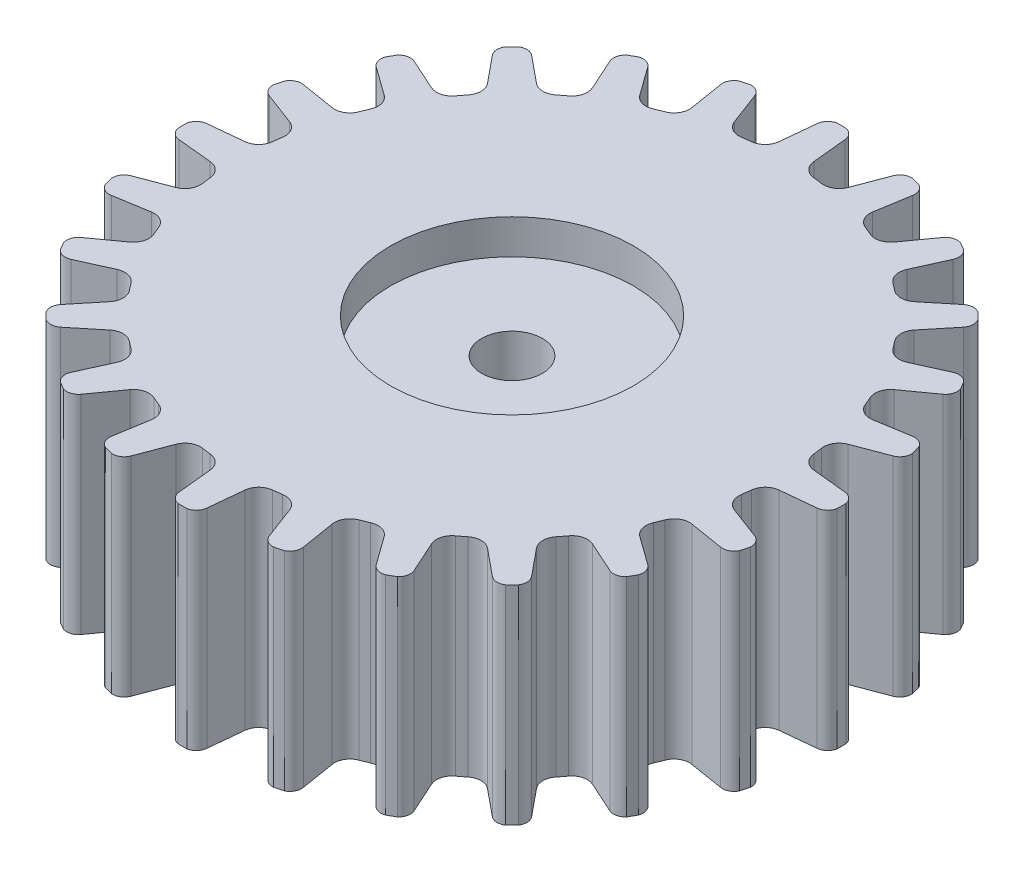
SolidWorks part; units mm, degrees
ref_plane "Front Plane" through (0, 0, 0) normal (0, 0, 1) x (1, 0, 0)
ref_plane "Top Plane" through (0, 0, 0) normal (0, 1, 0) x (1, 0, 0)
ref_plane "Right Plane" through (0, 0, 0) normal (1, 0, 0) x (0, 0, -1)
sketch "Sketch1" plane through (0, 0, 0) normal (0, 1, 0) x (1, 0, 0)
  circle A0 centre (0, 0) radius 2.45
  circle A1 centre (0, 0) radius 9.5
  dimension "D1" = 4.9
  dimension "D2" = 19
extrude "Boss-Extrude1" add sketch "Sketch1" along normal blind 6
sketch "Sketch2" plane through (0, 6, 0) normal (0, 1, 0) x (1, 0, 0)
  line L0 (0, 0) -> (0, 10.7871) construction
  line L1 (0.5, 8.2) -> (0.4, 9.2)
  line L2 (-0.5, 8.2) -> (-0.4, 9.2)
  line L3 (2.6053, 7.7912) -> (2.7675, 8.783)
  line L4 (1.6394, 8.05) -> (1.9948, 8.99)
  line L5 (4.533, 6.8514) -> (4.9464, 7.7674)
  line L6 (3.667, 7.3514) -> (4.2536, 8.1674)
  line L7 (6.1518, 5.4447) -> (6.7882, 6.2225)
  line L8 (5.4447, 6.1518) -> (6.2225, 6.7882)
  line L9 (7.3514, 3.667) -> (8.1674, 4.2536)
  line L10 (6.8514, 4.533) -> (7.7674, 4.9464)
  line L11 (8.05, 1.6394) -> (8.99, 1.9948)
  line L12 (7.7912, 2.6053) -> (8.783, 2.7675)
  line L13 (8.2, -0.5) -> (9.2, -0.4)
  line L14 (8.2, 0.5) -> (9.2, 0.4)
  line L15 (7.7912, -2.6053) -> (8.783, -2.7675)
  line L16 (8.05, -1.6394) -> (8.99, -1.9948)
  line L17 (6.8514, -4.533) -> (7.7674, -4.9464)
  line L18 (7.3514, -3.667) -> (8.1674, -4.2536)
  line L19 (5.4447, -6.1518) -> (6.2225, -6.7882)
  line L20 (6.1518, -5.4447) -> (6.7882, -6.2225)
  line L21 (3.667, -7.3514) -> (4.2536, -8.1674)
  line L22 (4.533, -6.8514) -> (4.9464, -7.7674)
  line L23 (1.6394, -8.05) -> (1.9948, -8.99)
  line L24 (2.6053, -7.7912) -> (2.7675, -8.783)
  line L25 (-0.5, -8.2) -> (-0.4, -9.2)
  line L26 (0.5, -8.2) -> (0.4, -9.2)
  line L27 (-2.6053, -7.7912) -> (-2.7675, -8.783)
  line L28 (-1.6394, -8.05) -> (-1.9948, -8.99)
  line L29 (-4.533, -6.8514) -> (-4.9464, -7.7674)
  line L30 (-3.667, -7.3514) -> (-4.2536, -8.1674)
  line L31 (-6.1518, -5.4447) -> (-6.7882, -6.2225)
  line L32 (-5.4447, -6.1518) -> (-6.2225, -6.7882)
  line L33 (-7.3514, -3.667) -> (-8.1674, -4.2536)
  line L34 (-6.8514, -4.533) -> (-7.7674, -4.9464)
  line L35 (-8.05, -1.6394) -> (-8.99, -1.9948)
  line L36 (-7.7912, -2.6053) -> (-8.783, -2.7675)
  line L37 (-8.2, 0.5) -> (-9.2, 0.4)
  line L38 (-8.2, -0.5) -> (-9.2, -0.4)
  line L39 (-7.7912, 2.6053) -> (-8.783, 2.7675)
  line L40 (-8.05, 1.6394) -> (-8.99, 1.9948)
  line L41 (-6.8514, 4.533) -> (-7.7674, 4.9464)
  line L42 (-7.3514, 3.667) -> (-8.1674, 4.2536)
  line L43 (-5.4447, 6.1518) -> (-6.2225, 6.7882)
  line L44 (-6.1518, 5.4447) -> (-6.7882, 6.2225)
  line L45 (-3.667, 7.3514) -> (-4.2536, 8.1674)
  line L46 (-4.533, 6.8514) -> (-4.9464, 7.7674)
  line L47 (-1.6394, 8.05) -> (-1.9948, 8.99)
  line L48 (-2.6053, 7.7912) -> (-2.7675, 8.783)
  arc A0 (2.8881, 7.3013) -> (3.1206, 7.205) centre (0, 0) cw
  arc A2 (0.9, 7.8) -> (1.1495, 7.7672) centre (0, 0) cw
  arc A3 (0.5, 8.2) -> (0.9, 7.8) centre (0.9444, 8.2444) ccw
  arc A4 (0, 9.5) -> (0.4, 9.2) centre (0.0622, 9.1662) cw
  arc A5 (-0.5, 8.2) -> (-0.9, 7.8) centre (-0.9444, 8.2444) cw
  arc A6 (0, 9.5) -> (-0.4, 9.2) centre (-0.0622, 9.1662) ccw
  arc A7 (2.6053, 7.7912) -> (2.8881, 7.3013) centre (3.0461, 7.7191) ccw
  arc A8 (2.4588, 9.1763) -> (2.7675, 8.783) centre (2.4324, 8.8378) cw
  arc A9 (1.6394, 8.05) -> (1.1495, 7.7672) centre (1.2216, 8.208) cw
  arc A10 (2.4588, 9.1763) -> (1.9948, 8.99) centre (2.3123, 8.87) ccw
  arc A11 (4.6794, 6.305) -> (4.879, 6.1518) centre (0, 0) cw
  arc A12 (4.533, 6.8514) -> (4.6794, 6.305) centre (4.9401, 6.6677) ccw
  arc A13 (4.75, 8.2272) -> (4.9464, 7.7674) centre (4.6369, 7.9071) cw
  arc A14 (3.667, 7.3514) -> (3.1206, 7.205) centre (3.3043, 7.6121) cw
  arc A15 (4.75, 8.2272) -> (4.2536, 8.1674) centre (4.5293, 7.9693) ccw
  arc A16 (6.1518, 4.879) -> (6.305, 4.6794) centre (0, 0) cw
  arc A17 (6.1518, 5.4447) -> (6.1518, 4.879) centre (6.4975, 5.1619) ccw
  arc A18 (6.7175, 6.7175) -> (6.7882, 6.2225) centre (6.5254, 6.4375) cw
  arc A19 (5.4447, 6.1518) -> (4.879, 6.1518) centre (5.1619, 6.4975) cw
  arc A20 (6.7175, 6.7175) -> (6.2225, 6.7882) centre (6.4375, 6.5254) ccw
  arc A21 (7.205, 3.1206) -> (7.3013, 2.8881) centre (0, 0) cw
  arc A22 (7.3514, 3.667) -> (7.205, 3.1206) centre (7.6121, 3.3043) ccw
  arc A23 (8.2272, 4.75) -> (8.1674, 4.2536) centre (7.9693, 4.5293) cw
  arc A24 (6.8514, 4.533) -> (6.305, 4.6794) centre (6.6677, 4.9401) cw
  arc A25 (8.2272, 4.75) -> (7.7674, 4.9464) centre (7.9071, 4.6369) ccw
  arc A26 (7.7672, 1.1495) -> (7.8, 0.9) centre (0, 0) cw
  arc A27 (8.05, 1.6394) -> (7.7672, 1.1495) centre (8.208, 1.2216) ccw
  arc A28 (9.1763, 2.4588) -> (8.99, 1.9948) centre (8.87, 2.3123) cw
  arc A29 (7.7912, 2.6053) -> (7.3013, 2.8881) centre (7.7191, 3.0461) cw
  arc A30 (9.1763, 2.4588) -> (8.783, 2.7675) centre (8.8378, 2.4324) ccw
  arc A31 (7.8, -0.9) -> (7.7672, -1.1495) centre (0, 0) cw
  arc A32 (8.2, -0.5) -> (7.8, -0.9) centre (8.2444, -0.9444) ccw
  arc A33 (9.5, 0) -> (9.2, -0.4) centre (9.1662, -0.0622) cw
  arc A34 (8.2, 0.5) -> (7.8, 0.9) centre (8.2444, 0.9444) cw
  arc A35 (9.5, 0) -> (9.2, 0.4) centre (9.1662, 0.0622) ccw
  arc A36 (7.3013, -2.8881) -> (7.205, -3.1206) centre (0, 0) cw
  arc A37 (7.7912, -2.6053) -> (7.3013, -2.8881) centre (7.7191, -3.0461) ccw
  arc A38 (9.1763, -2.4588) -> (8.783, -2.7675) centre (8.8378, -2.4324) cw
  arc A39 (8.05, -1.6394) -> (7.7672, -1.1495) centre (8.208, -1.2216) cw
  arc A40 (9.1763, -2.4588) -> (8.99, -1.9948) centre (8.87, -2.3123) ccw
  arc A41 (6.305, -4.6794) -> (6.1518, -4.879) centre (0, 0) cw
  arc A42 (6.8514, -4.533) -> (6.305, -4.6794) centre (6.6677, -4.9401) ccw
  arc A43 (8.2272, -4.75) -> (7.7674, -4.9464) centre (7.9071, -4.6369) cw
  arc A44 (7.3514, -3.667) -> (7.205, -3.1206) centre (7.6121, -3.3043) cw
  arc A45 (8.2272, -4.75) -> (8.1674, -4.2536) centre (7.9693, -4.5293) ccw
  arc A46 (4.879, -6.1518) -> (4.6794, -6.305) centre (0, 0) cw
  arc A47 (5.4447, -6.1518) -> (4.879, -6.1518) centre (5.1619, -6.4975) ccw
  arc A48 (6.7175, -6.7175) -> (6.2225, -6.7882) centre (6.4375, -6.5254) cw
  arc A49 (6.1518, -5.4447) -> (6.1518, -4.879) centre (6.4975, -5.1619) cw
  arc A50 (6.7175, -6.7175) -> (6.7882, -6.2225) centre (6.5254, -6.4375) ccw
  arc A51 (3.1206, -7.205) -> (2.8881, -7.3013) centre (0, 0) cw
  arc A52 (3.667, -7.3514) -> (3.1206, -7.205) centre (3.3043, -7.6121) ccw
  arc A53 (4.75, -8.2272) -> (4.2536, -8.1674) centre (4.5293, -7.9693) cw
  arc A54 (4.533, -6.8514) -> (4.6794, -6.305) centre (4.9401, -6.6677) cw
  arc A55 (4.75, -8.2272) -> (4.9464, -7.7674) centre (4.6369, -7.9071) ccw
  arc A56 (1.1495, -7.7672) -> (0.9, -7.8) centre (0, 0) cw
  arc A57 (1.6394, -8.05) -> (1.1495, -7.7672) centre (1.2216, -8.208) ccw
  arc A58 (2.4588, -9.1763) -> (1.9948, -8.99) centre (2.3123, -8.87) cw
  arc A59 (2.6053, -7.7912) -> (2.8881, -7.3013) centre (3.0461, -7.7191) cw
  arc A60 (2.4588, -9.1763) -> (2.7675, -8.783) centre (2.4324, -8.8378) ccw
  arc A61 (-0.9, -7.8) -> (-1.1495, -7.7672) centre (0, 0) cw
  arc A62 (-0.5, -8.2) -> (-0.9, -7.8) centre (-0.9444, -8.2444) ccw
  arc A63 (0, -9.5) -> (-0.4, -9.2) centre (-0.0622, -9.1662) cw
  arc A64 (0.5, -8.2) -> (0.9, -7.8) centre (0.9444, -8.2444) cw
  arc A65 (0, -9.5) -> (0.4, -9.2) centre (0.0622, -9.1662) ccw
  arc A66 (-2.8881, -7.3013) -> (-3.1206, -7.205) centre (0, 0) cw
  arc A67 (-2.6053, -7.7912) -> (-2.8881, -7.3013) centre (-3.0461, -7.7191) ccw
  arc A68 (-2.4588, -9.1763) -> (-2.7675, -8.783) centre (-2.4324, -8.8378) cw
  arc A69 (-1.6394, -8.05) -> (-1.1495, -7.7672) centre (-1.2216, -8.208) cw
  arc A70 (-2.4588, -9.1763) -> (-1.9948, -8.99) centre (-2.3123, -8.87) ccw
  arc A71 (-4.6794, -6.305) -> (-4.879, -6.1518) centre (0, 0) cw
  arc A72 (-4.533, -6.8514) -> (-4.6794, -6.305) centre (-4.9401, -6.6677) ccw
  arc A73 (-4.75, -8.2272) -> (-4.9464, -7.7674) centre (-4.6369, -7.9071) cw
  arc A74 (-3.667, -7.3514) -> (-3.1206, -7.205) centre (-3.3043, -7.6121) cw
  arc A75 (-4.75, -8.2272) -> (-4.2536, -8.1674) centre (-4.5293, -7.9693) ccw
  arc A76 (-6.1518, -4.879) -> (-6.305, -4.6794) centre (0, 0) cw
  arc A77 (-6.1518, -5.4447) -> (-6.1518, -4.879) centre (-6.4975, -5.1619) ccw
  arc A78 (-6.7175, -6.7175) -> (-6.7882, -6.2225) centre (-6.5254, -6.4375) cw
  arc A79 (-5.4447, -6.1518) -> (-4.879, -6.1518) centre (-5.1619, -6.4975) cw
  arc A80 (-6.7175, -6.7175) -> (-6.2225, -6.7882) centre (-6.4375, -6.5254) ccw
  arc A81 (-7.205, -3.1206) -> (-7.3013, -2.8881) centre (0, 0) cw
  arc A82 (-7.3514, -3.667) -> (-7.205, -3.1206) centre (-7.6121, -3.3043) ccw
  arc A83 (-8.2272, -4.75) -> (-8.1674, -4.2536) centre (-7.9693, -4.5293) cw
  arc A84 (-6.8514, -4.533) -> (-6.305, -4.6794) centre (-6.6677, -4.9401) cw
  arc A85 (-8.2272, -4.75) -> (-7.7674, -4.9464) centre (-7.9071, -4.6369) ccw
  arc A86 (-7.7672, -1.1495) -> (-7.8, -0.9) centre (0, 0) cw
  arc A87 (-8.05, -1.6394) -> (-7.7672, -1.1495) centre (-8.208, -1.2216) ccw
  arc A88 (-9.1763, -2.4588) -> (-8.99, -1.9948) centre (-8.87, -2.3123) cw
  arc A89 (-7.7912, -2.6053) -> (-7.3013, -2.8881) centre (-7.7191, -3.0461) cw
  arc A90 (-9.1763, -2.4588) -> (-8.783, -2.7675) centre (-8.8378, -2.4324) ccw
  arc A91 (-7.8, 0.9) -> (-7.7672, 1.1495) centre (0, 0) cw
  arc A92 (-8.2, 0.5) -> (-7.8, 0.9) centre (-8.2444, 0.9444) ccw
  arc A93 (-9.5, 0) -> (-9.2, 0.4) centre (-9.1662, 0.0622) cw
  arc A94 (-8.2, -0.5) -> (-7.8, -0.9) centre (-8.2444, -0.9444) cw
  arc A95 (-9.5, 0) -> (-9.2, -0.4) centre (-9.1662, -0.0622) ccw
  arc A96 (-7.3013, 2.8881) -> (-7.205, 3.1206) centre (0, 0) cw
  arc A97 (-7.7912, 2.6053) -> (-7.3013, 2.8881) centre (-7.7191, 3.0461) ccw
  arc A98 (-9.1763, 2.4588) -> (-8.783, 2.7675) centre (-8.8378, 2.4324) cw
  arc A99 (-8.05, 1.6394) -> (-7.7672, 1.1495) centre (-8.208, 1.2216) cw
  arc A100 (-9.1763, 2.4588) -> (-8.99, 1.9948) centre (-8.87, 2.3123) ccw
  arc A101 (-6.305, 4.6794) -> (-6.1518, 4.879) centre (0, 0) cw
  arc A102 (-6.8514, 4.533) -> (-6.305, 4.6794) centre (-6.6677, 4.9401) ccw
  arc A103 (-8.2272, 4.75) -> (-7.7674, 4.9464) centre (-7.9071, 4.6369) cw
  arc A104 (-7.3514, 3.667) -> (-7.205, 3.1206) centre (-7.6121, 3.3043) cw
  arc A105 (-8.2272, 4.75) -> (-8.1674, 4.2536) centre (-7.9693, 4.5293) ccw
  arc A106 (-4.879, 6.1518) -> (-4.6794, 6.305) centre (0, 0) cw
  arc A107 (-5.4447, 6.1518) -> (-4.879, 6.1518) centre (-5.1619, 6.4975) ccw
  arc A108 (-6.7175, 6.7175) -> (-6.2225, 6.7882) centre (-6.4375, 6.5254) cw
  arc A109 (-6.1518, 5.4447) -> (-6.1518, 4.879) centre (-6.4975, 5.1619) cw
  arc A110 (-6.7175, 6.7175) -> (-6.7882, 6.2225) centre (-6.5254, 6.4375) ccw
  arc A111 (-3.1206, 7.205) -> (-2.8881, 7.3013) centre (0, 0) cw
  arc A112 (-3.667, 7.3514) -> (-3.1206, 7.205) centre (-3.3043, 7.6121) ccw
  arc A113 (-4.75, 8.2272) -> (-4.2536, 8.1674) centre (-4.5293, 7.9693) cw
  arc A114 (-4.533, 6.8514) -> (-4.6794, 6.305) centre (-4.9401, 6.6677) cw
  arc A115 (-4.75, 8.2272) -> (-4.9464, 7.7674) centre (-4.6369, 7.9071) ccw
  arc A116 (-1.1495, 7.7672) -> (-0.9, 7.8) centre (0, 0) cw
  arc A117 (-1.6394, 8.05) -> (-1.1495, 7.7672) centre (-1.2216, 8.208) ccw
  arc A118 (-2.4588, 9.1763) -> (-1.9948, 8.99) centre (-2.3123, 8.87) cw
  arc A119 (-2.6053, 7.7912) -> (-2.8881, 7.3013) centre (-3.0461, 7.7191) cw
  arc A120 (-2.4588, 9.1763) -> (-2.7675, 8.783) centre (-2.4324, 8.8378) ccw
  circle A121 centre (0, 0) radius 9.5 construction
  circle A132 centre (0, 0) radius 11.1781
  point P296 (0, 0)
  dimension "D7" = 24
  dimension "D1" = 0.4
  dimension "D2" = 0.1
  dimension "D3" = 1
  dimension "D4" = 0.3
  dimension "D5" = 0.4
  dimension "D6" = 0.4
extrude "Cut-Extrude1" cut sketch "Sketch2" against normal up to next
sketch "Sketch3" plane through (0, 6, 0) normal (0, 1, 0) x (1, 0, 0)
  circle A0 centre (0, 0) radius 2.45 construction
  circle A1 centre (0, 0) radius 2.45
  circle A2 centre (0, 0) radius 0.875
  dimension "D1" = 1.75
extrude "Boss-Extrude2" add sketch "Sketch3" against normal blind 3.25
sketch "Sketch4" plane through (0, 6, 0) normal (0, 1, 0) x (1, 0, 0)
  circle A0 centre (0, 0) radius 3.5
  dimension "D1" = 7
extrude "Cut-Extrude2" cut sketch "Sketch4" against normal blind 1
